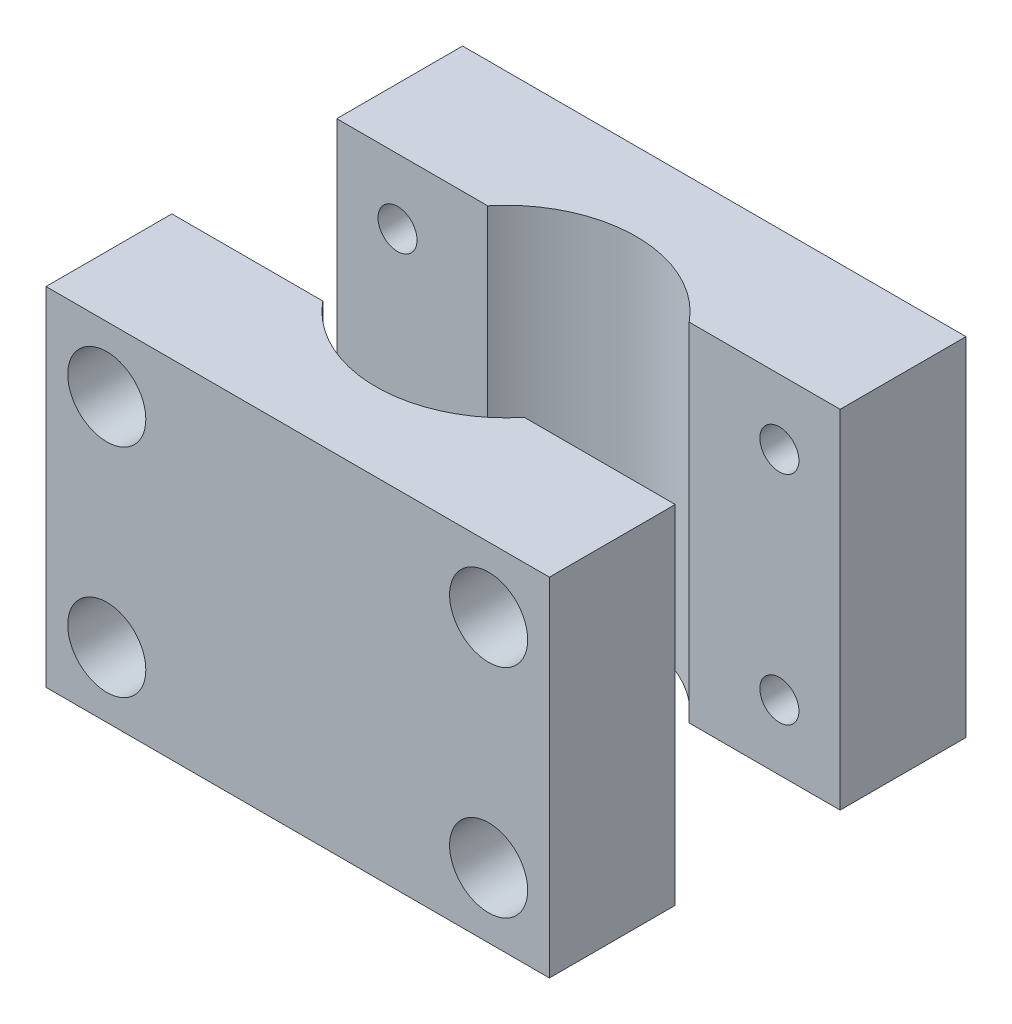
SolidWorks part; units mm, degrees
material "3D printed plastic"
ref_plane "Front Plane" through (0, 0, 0) normal (0, 0, 1) x (1, 0, 0)
ref_plane "Top Plane" through (0, 0, 0) normal (0, 1, 0) x (1, 0, 0)
ref_plane "Right Plane" through (0, 0, 0) normal (1, 0, 0) x (0, 0, -1)
sketch "Sketch1" plane through (0, 0, 0) normal (0, 1, 0) x (1, 0, 0)
  line L0 (29, -9.5) -> (29, -24)
  line L1 (-29, 24) -> (29, 24)
  line L2 (-29, 24) -> (-29, 9.5)
  line L3 (-29, -24) -> (29, -24)
  line L4 (29, 24) -> (29, 9.5)
  line L5 (-29, 9.5) -> (-11.6082, 9.5)
  line L6 (11.6082, -9.5) -> (29, -9.5)
  line L7 (-29, -9.5) -> (-11.6082, -9.5)
  line L9 (-29, -9.5) -> (-29, -24)
  line L10 (11.6082, 9.5) -> (29, 9.5)
  arc A0 (11.6082, 9.5) -> (-11.6082, 9.5) centre (0, 0) ccw
  arc A1 (-11.6082, -9.5) -> (11.6082, -9.5) centre (0, 0) ccw
  dimension "D1" = 15
  dimension "D2" = 19
  dimension "D3" = 48
  dimension "D4" = 58
extrude "Boss-Extrude1" add sketch "Sketch1" along normal mid plane 40
sketch "Sketch2" plane through (0, 0, 24) normal (0, 0, 1) x (1, 0, 0)
  line L0 (-22, 0) -> (22, 0) construction
  line L1 (22, 12.5) -> (22, -12.5) construction
  line L2 (29, 20) -> (29, -20) construction
  line L3 (0, 0) -> (0, 4.8868) construction
  line L4 (-22, 12.5) -> (-22, -12.5) construction
  circle A0 centre (22, 12.5) radius 2.25
  circle A1 centre (22, -12.5) radius 2.25
  circle A2 centre (-22, -12.5) radius 2.25
  circle A3 centre (-22, 12.5) radius 2.25
  dimension "D2" = 4.5
  dimension "D1" = 25
  dimension "D3" = 7
extrude "Cut-Extrude1" cut sketch "Sketch2" against normal through all
sketch "Sketch3" plane through (0, 0, 24) normal (0, 0, 1) x (1, 0, 0)
  circle A0 centre (22, 12.5) radius 4.5
  circle A1 centre (22, -12.5) radius 4.5
  circle A2 centre (-22, -12.5) radius 4.5
  circle A3 centre (-22, 12.5) radius 4.5
  dimension "D1" = 9
extrude "Cut-Extrude2" cut sketch "Sketch3" against normal blind 7
sketch "Sketch4" plane through (0, 0, 17) normal (0, 0, 1) x (1, 0, 0)
  line L1 (22, 8.1699) -> (25.75, 10.3349)
  line L2 (25.75, 10.3349) -> (25.75, 14.6651)
  line L3 (25.75, 14.6651) -> (22, 16.8301)
  line L4 (22, 16.8301) -> (18.25, 14.6651)
  line L5 (18.25, 14.6651) -> (18.25, 10.3349)
  line L6 (18.25, 10.3349) -> (22, 8.1699)
  line L7 (22, -16.8301) -> (25.75, -14.6651)
  line L8 (25.75, -14.6651) -> (25.75, -10.3349)
  line L9 (25.75, -10.3349) -> (22, -8.1699)
  line L10 (22, -8.1699) -> (18.25, -10.3349)
  line L11 (18.25, -10.3349) -> (18.25, -14.6651)
  line L12 (18.25, -14.6651) -> (22, -16.8301)
  line L13 (-22, -16.8301) -> (-18.25, -14.6651)
  line L14 (-18.25, -14.6651) -> (-18.25, -10.3349)
  line L15 (-18.25, -10.3349) -> (-22, -8.1699)
  line L16 (-22, -8.1699) -> (-25.75, -10.3349)
  line L17 (-25.75, -10.3349) -> (-25.75, -14.6651)
  line L18 (-25.75, -14.6651) -> (-22, -16.8301)
  line L19 (-22, 8.1699) -> (-18.25, 10.3349)
  line L20 (-18.25, 10.3349) -> (-18.25, 14.6651)
  line L21 (-18.25, 14.6651) -> (-22, 16.8301)
  line L22 (-22, 16.8301) -> (-25.75, 14.6651)
  line L23 (-25.75, 14.6651) -> (-25.75, 10.3349)
  line L24 (-25.75, 10.3349) -> (-22, 8.1699)
  circle A0 centre (22, 12.5) radius 3.75 construction
  circle A1 centre (22, -12.5) radius 3.75 construction
  circle A2 centre (-22, -12.5) radius 3.75 construction
  circle A3 centre (-22, 12.5) radius 3.75 construction
  dimension "D1" = 7.5
extrude "Cut-Extrude3" cut sketch "Sketch4" against normal through all from offset 35
